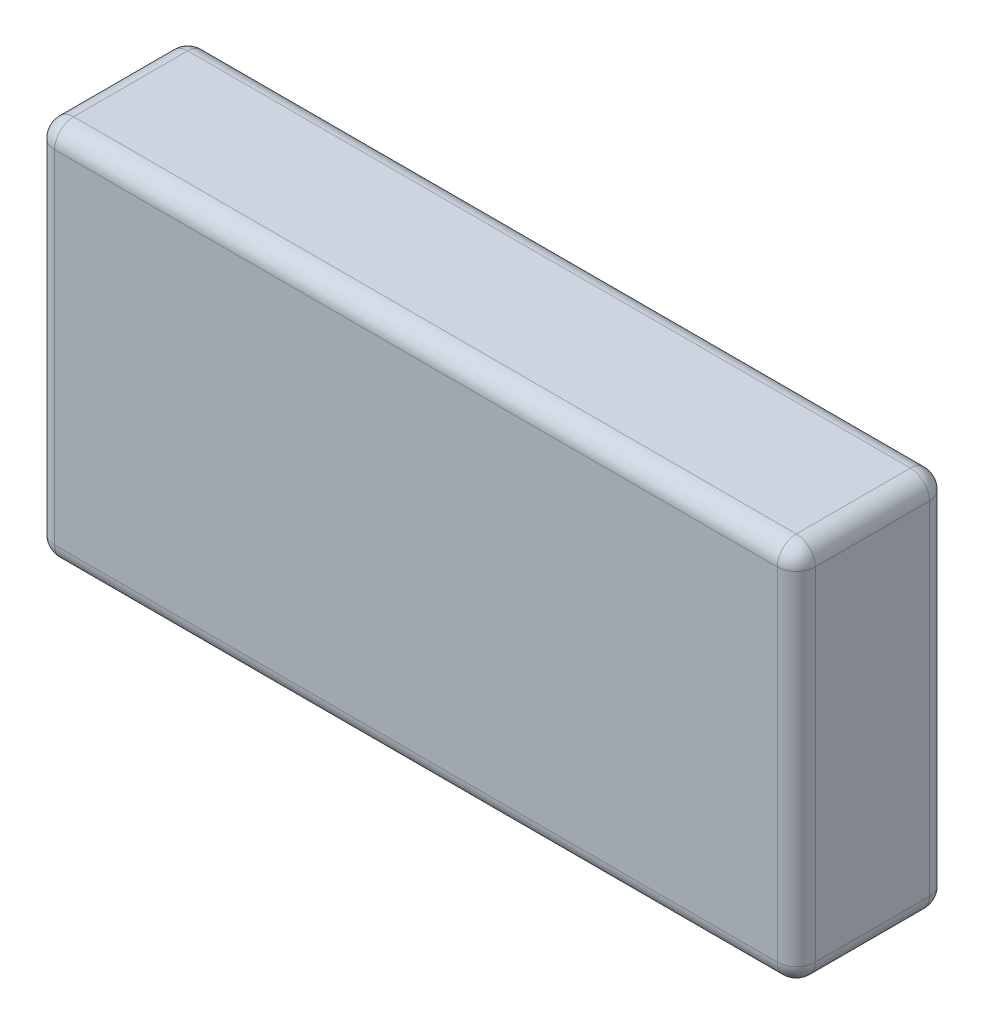
SolidWorks part; units mm, degrees
ref_plane "Front Plane" through (0, 0, 0) normal (0, 0, 1) x (1, 0, 0)
ref_plane "Top Plane" through (0, 0, 0) normal (0, 1, 0) x (1, 0, 0)
ref_plane "Right Plane" through (0, 0, 0) normal (1, 0, 0) x (0, 0, -1)
sketch "Sketch1" plane through (0, 0, 0) normal (0, 1, 0) x (1, 0, 0)
  line L1 (-5, 1) -> (5, 1)
  line L2 (-5, 1) -> (-5, -1)
  line L3 (-5, -1) -> (5, -1)
  line L4 (5, 1) -> (5, -1)
  line L5 (-5, 1) -> (5, -1) construction
  line L6 (-5, -1) -> (5, 1) construction
  point P0 (0, 0)
  dimension "D1" = 2
  dimension "D2" = 10
extrude "Boss-Extrude1" add sketch "Sketch1" along normal blind 5
fillet "Fillet1" radius 0.25 12 edges at (5, 0, 0) (5, 5, 0) (-5, 5, 0) (-5, 0, 0) (5, 2.5, -1) (0, 5, -1) (-5, 2.5, -1) (0, 0, -1) (-5, 2.5, 1) (0, 5, 1) (5, 2.5, 1) (0, 0, 1)
